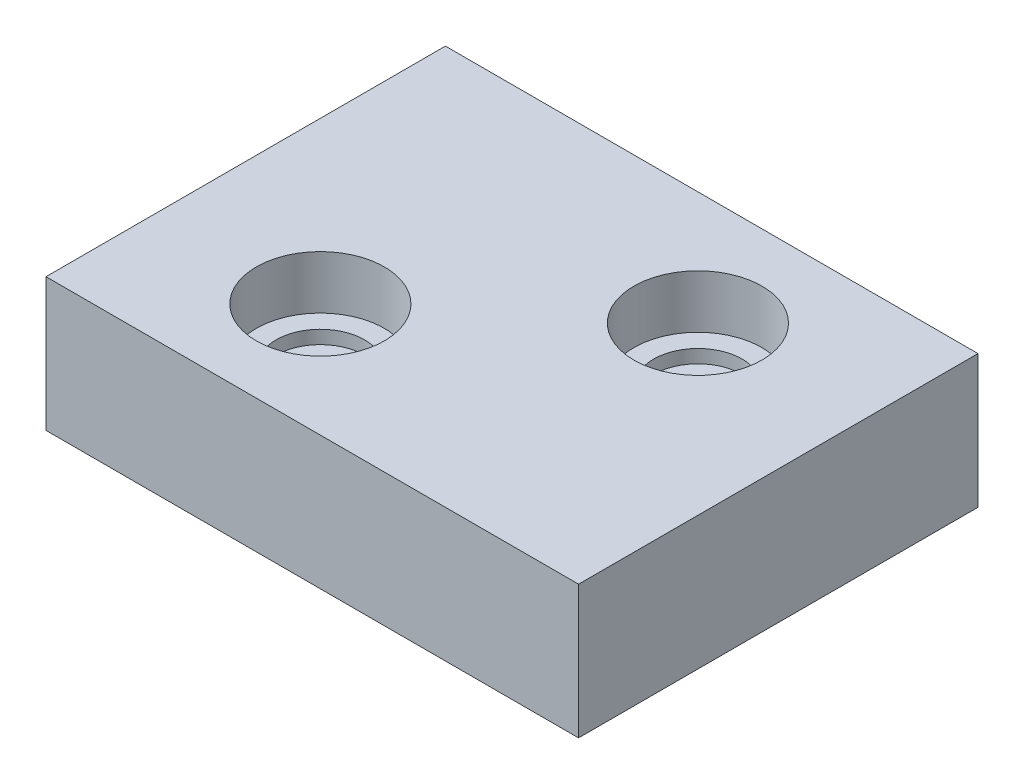
SolidWorks part; units mm, degrees
ref_plane "Front Plane" through (0, 0, 0) normal (0, 0, 1) x (1, 0, 0)
ref_plane "Top Plane" through (0, 0, 0) normal (0, 1, 0) x (1, 0, 0)
ref_plane "Right Plane" through (0, 0, 0) normal (1, 0, 0) x (0, 0, -1)
sketch "Sketch1" plane through (0, 0, 0) normal (0, 1, 0) x (1, 0, 0)
  line L1 (-20, -15) -> (20, -15)
  line L2 (-20, -15) -> (-20, 15)
  line L3 (-20, 15) -> (20, 15)
  line L4 (20, -15) -> (20, 15)
  line L5 (-20, -15) -> (20, 15) construction
  line L6 (-20, 15) -> (20, -15) construction
  point P0 (0, 0)
  dimension "D1" = 40
  dimension "D2" = 30
extrude "Boss-Extrude1" add sketch "Sketch1" along normal blind 10
sketch "Sketch2" plane through (0, 0, 0) normal (0, -1, 0) x (-1, 0, 0)
  line L0 (0, -15) -> (0, 15) construction
  line L1 (20, -15) -> (-20, -15) construction
  line L2 (-20, 15) -> (20, 15) construction
  line L3 (20, 0) -> (-20, 0) construction
  line L4 (20, 15) -> (20, -15) construction
  line L5 (-20, -15) -> (-20, 15) construction
  line L6 (20, -15) -> (-20, 15) construction
  line L7 (-20, -15) -> (20, 15) construction
  circle A0 centre (-13.3333, -10) radius 1.55
  circle A1 centre (13.3333, -10) radius 1.55
  circle A2 centre (-13.3333, 10) radius 1.55
  circle A3 centre (13.3333, 10) radius 1.55
  dimension "D1" = 3.1
  dimension "D2" = 5
extrude "Cut-Extrude1" cut sketch "Sketch2" against normal blind 4
sketch "Sketch3" plane through (0, 10, 0) normal (0, 1, 0) x (1, 0, 0)
  line L0 (20, -15) -> (20, 15) construction
  line L4 (-20, -15) -> (20, -15) construction
  line L8 (7.5, -6.465) -> (7.5, 6.4636) construction
  line L11 (-20, 15) -> (-20, -15) construction
  circle A0 centre (-7.9286, -6.465) radius 4.8125
  circle A1 centre (7.5, 6.4636) radius 4.8125
  dimension "D1" = 9.625
  dimension "D3" = 8.535
  dimension "D6" = 9.625
  dimension "D2" = 12.0714
  dimension "D4" = 12.5
  dimension "D5" = 12.9286
extrude "Cut-Extrude2" cut sketch "Sketch3" against normal blind 4
sketch "Sketch4" plane through (0, 6, 0) normal (0, 1, 0) x (1, 0, 0)
  circle A0 centre (-7.9286, -6.465) radius 3.325
  circle A1 centre (7.5, 6.4636) radius 3.325
  dimension "D1" = 6.65
  dimension "D2" = 6.65
extrude "Cut-Extrude3" cut sketch "Sketch4" against normal blind 1
